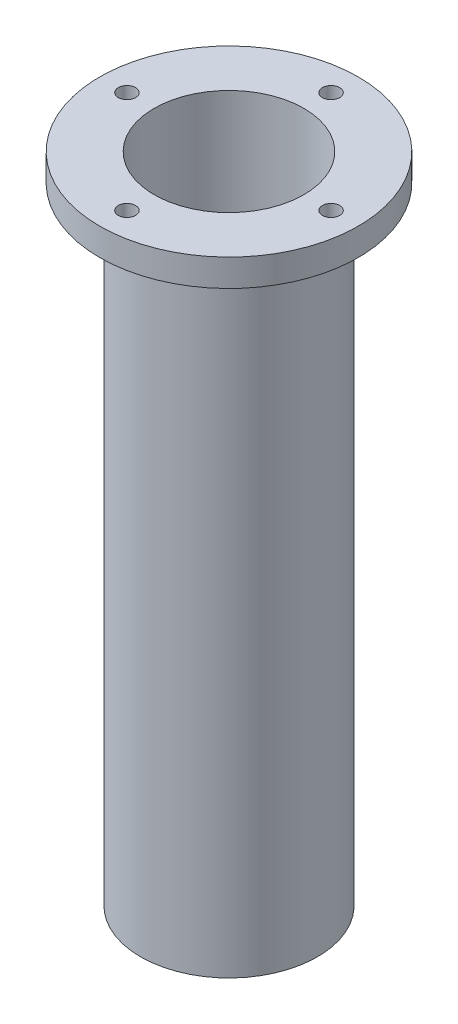
SolidWorks part; units mm, degrees
ref_plane "Front Plane" through (0, 0, 0) normal (0, 0, 1) x (1, 0, 0)
ref_plane "Top Plane" through (0, 0, 0) normal (0, 1, 0) x (1, 0, 0)
ref_plane "Right Plane" through (0, 0, 0) normal (1, 0, 0) x (0, 0, -1)
sketch "Sketch1" plane through (0, 0, 0) normal (0, 1, 0) x (1, 0, 0)
  circle A0 centre (0, 0) radius 17.4625
  circle A1 centre (0, 0) radius 20.6375
  dimension "D1" = 34.925
  dimension "D2" = 3.175
extrude "Boss-Extrude1" add sketch "Sketch1" along normal blind 152.4
sketch "Sketch2" plane through (0, 152.4, 0) normal (0, 1, 0) x (1, 0, 0)
  circle A0 centre (0, 0) radius 30.1625
  circle A1 centre (0, 0) radius 17.4625 construction
  circle A2 centre (0, 0) radius 17.4625
  dimension "D1" = 12.7
extrude "Boss-Extrude2" add sketch "Sketch2" against normal blind 6.35
hole_wizard "#10-32 Tapped Hole1" positions "Sketch4" profile "Sketch6" tap size "#10-32" standard "ANSI Inch" end condition up to next
sketch "Sketch4" plane through (0, 152.4, 0) normal (0, 1, 0) x (1, 0, 0)
  circle A0 centre (0, 0) radius 23.8125 construction
  circle A1 centre (0, 0) radius 17.4625 construction
  point P0 (-23.8125, 0)
  point P2 (0, 23.8125)
  point P4 (23.8125, 0)
  point P6 (0, -23.8125)
  point P13 (0, 0)
  dimension "D1" = 6.35
sketch "Sketch6" plane through (-23.8125, 152.4, 0) normal (1, 0, 0) x (0, 0, 1)
  line L0 (0, 0) -> (0, 6.35)
  line L1 (0, 6.35) -> (2.0193, 6.35)
  line L2 (2.0193, 6.35) -> (2.0193, 0)
  line L5 (2.0193, 0) -> (0, 0)
  line L11 (0, -6.35) -> (0, 107.95) construction
  dimension "Thru Tap Drill Dia." = 4.0386
  dimension "Thru Tap Drill Depth" = 6.35
cosmetic thread "Hole Thread1" parameters "D2"=4.826
cosmetic thread "Hole Thread2" parameters "D2"=4.826
cosmetic thread "Hole Thread3" parameters "D2"=4.826
cosmetic thread "Hole Thread4" parameters "D2"=4.826
